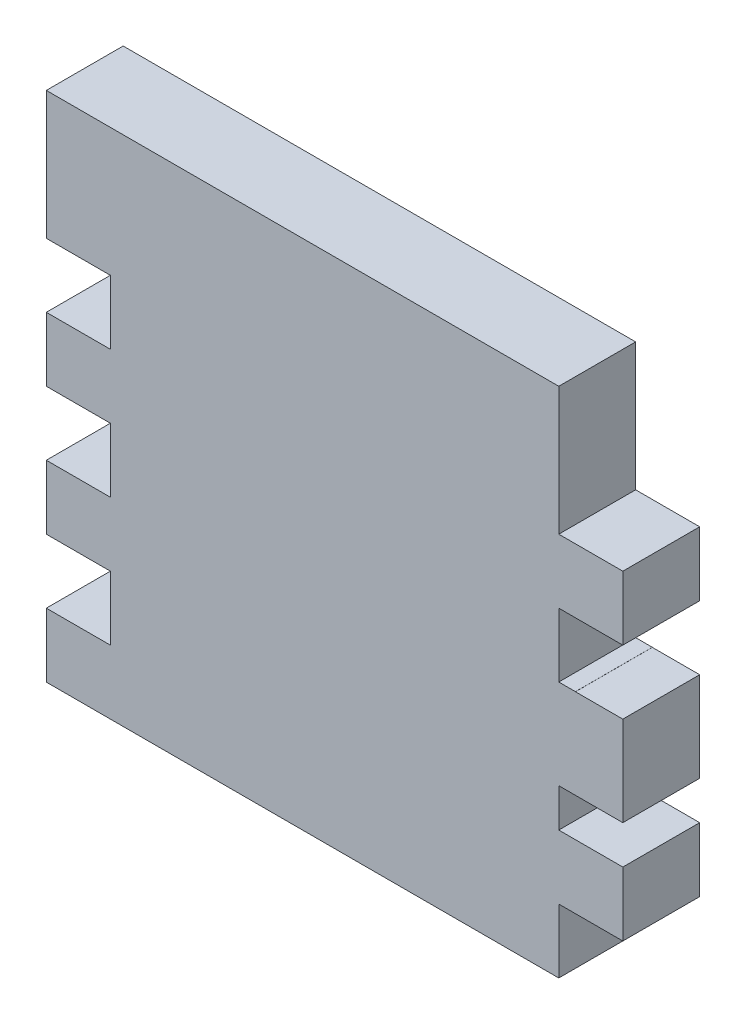
SolidWorks part; units mm, degrees
ref_plane "Front Plane" through (0, 0, 0) normal (0, 0, 1) x (1, 0, 0)
ref_plane "Top Plane" through (0, 0, 0) normal (0, 1, 0) x (1, 0, 0)
ref_plane "Right Plane" through (0, 0, 0) normal (1, 0, 0) x (0, 0, -1)
sketch "Sketch1" plane through (0, 0, 0) normal (0, 0, 1) x (1, 0, 0)
  line L1 (-14.4127, 5.9138) -> (30.5873, 5.9138)
  line L2 (-14.4127, 5.9138) -> (-14.4127, -34.0862)
  line L3 (-14.4127, -34.0862) -> (30.5873, -34.0862)
  line L4 (30.5873, 5.9138) -> (30.5873, -34.0862)
  dimension "D1" = 45
  dimension "D2" = 40
extrude "Boss-Extrude1" add sketch "Sketch1" along normal blind 6
sketch "Sketch2" plane through (0, 0, 6) normal (0, 0, 1) x (1, 0, 0)
  line L0 (-14.4127, 5.9138) -> (-14.4127, -34.0862) construction
  line L1 (-14.4127, -4.0862) -> (-9.4127, -4.0862)
  line L2 (-14.4127, -4.0862) -> (-14.4127, -9.0862)
  line L3 (-14.4127, -9.0862) -> (-9.4127, -9.0862)
  line L4 (-9.4127, -4.0862) -> (-9.4127, -9.0862)
  line L5 (-14.4127, -34.0862) -> (30.5873, -34.0862) construction
  line L6 (-14.4127, -24.0862) -> (-9.4127, -24.0862)
  line L7 (-14.4127, -24.0862) -> (-14.4127, -29.0862)
  line L8 (-14.4127, -29.0862) -> (-9.4127, -29.0862)
  line L9 (-9.4127, -24.0862) -> (-9.4127, -29.0862)
  line L10 (-14.4127, -14.0862) -> (-9.4127, -14.0862)
  line L11 (-14.4127, -14.0862) -> (-14.4127, -19.0862)
  line L12 (-14.4127, -19.0862) -> (-9.4127, -19.0862)
  line L13 (-9.4127, -14.0862) -> (-9.4127, -19.0862)
  line L14 (30.5873, -34.0862) -> (30.5873, 5.9138) construction
  line L15 (30.5873, 5.9138) -> (26.8891, 5.9138)
  line L16 (30.5873, 5.9138) -> (30.5873, -4.0862)
  line L17 (30.5873, -4.0862) -> (26.8891, -4.0862)
  line L18 (26.8891, 5.9138) -> (26.8891, -4.0862)
  line L19 (30.5873, -14.0862) -> (26.8891, -14.0862)
  line L20 (30.5873, -14.0862) -> (30.5873, -9.0862)
  line L21 (30.5873, -9.0862) -> (26.8891, -9.0862)
  line L22 (26.8891, -14.0862) -> (26.8891, -9.0862)
  line L24 (30.5873, -24.0862) -> (26.8891, -24.0862)
  line L25 (30.5873, -24.0862) -> (30.5873, -21.0862)
  line L26 (30.5873, -21.0862) -> (26.8891, -21.0862)
  line L27 (26.8891, -24.0862) -> (26.8891, -21.0862)
  line L28 (30.5873, -24.0862) -> (26.8891, -24.0862)
  line L29 (30.5873, -24.0862) -> (30.5873, -29.0862)
  line L30 (30.5873, -29.0862) -> (26.8891, -29.0862)
  line L31 (26.8891, -24.0862) -> (26.8891, -29.0862)
  line M22 (-14.4127, 5.9138) -> (-14.4127, -34.0862)
  line M24 (30.5873, -34.0862) -> (30.5873, 5.9138)
  line M25 (30.5873, 5.9138) -> (-14.4127, 5.9138)
  dimension "D1" = 5
  dimension "D2" = 5
  dimension "D3" = 5
  dimension "D4" = 5
  dimension "D5" = 5
  dimension "D6" = 5
  dimension "D7" = 5
  dimension "D8" = 5
  dimension "D9" = 5
  dimension "D10" = 10
  dimension "D11" = 5
  dimension "D12" = 7
  dimension "D13" = 5
  dimension "D14" = 5
  dimension "D15" = 5
  dimension "D16" = 3
extrude "Cut-Extrude1" cut sketch "Sketch2" against normal blind 6 contours L4 L1 L3 M22 | L13 L10 L12 M22 | L9 L6 L8 M22 | L18 L17 M25 M24 | L22 L19 L21 M24 | L27 L24 L26 M24
sketch "Sketch3" plane through (0, 0, 6) normal (0, 0, 1) x (1, 0, 0)
  line L1 (30.5873, -34.0862) -> (25.5873, -34.0862)
  line L2 (30.5873, -34.0862) -> (30.5873, -29.0862)
  line L3 (30.5873, -29.0862) -> (25.5873, -29.0862)
  line L4 (25.5873, -34.0862) -> (25.5873, -29.0862)
  dimension "D1" = 5
  dimension "D2" = 5
extrude "Cut-Extrude2" cut sketch "Sketch3" against normal blind 6 contours L2 L1 L4 L3
sketch "Sketch4" plane through (0, 0, 6) normal (0, 0, 1) x (1, 0, 0)
  line L0 (26.8891, 5.9138) -> (-14.4127, 5.9138) construction
  line L1 (30.5873, -9.0862) -> (25.5873, -9.0862)
  line L2 (30.5873, -9.0862) -> (30.5873, -14.079)
  line L3 (30.5873, -14.079) -> (25.5873, -14.079)
  line L4 (25.5873, -9.0862) -> (25.5873, -14.079)
  line L5 (30.5873, -4.0862) -> (25.5873, -4.0862)
  line L6 (30.5873, -4.0862) -> (30.5873, 5.9138)
  line L7 (30.5873, 5.9138) -> (25.5873, 5.9138)
  line L8 (25.5873, -4.0862) -> (25.5873, 5.9138)
  line L10 (30.5873, -21.0862) -> (25.5873, -21.0862)
  line L11 (30.5873, -21.0862) -> (30.5873, -24.0862)
  line L12 (30.5873, -24.0862) -> (25.5873, -24.0862)
  line L13 (25.5873, -21.0862) -> (25.5873, -24.0862)
  dimension "D1" = 5
  dimension "D2" = 5
  dimension "D3" = 3
extrude "Cut-Extrude3" cut sketch "Sketch4" against normal blind 6 contours L6 L5 L8 L7 | L2 L1 L4 L3 | L11 L10 L13 L12
